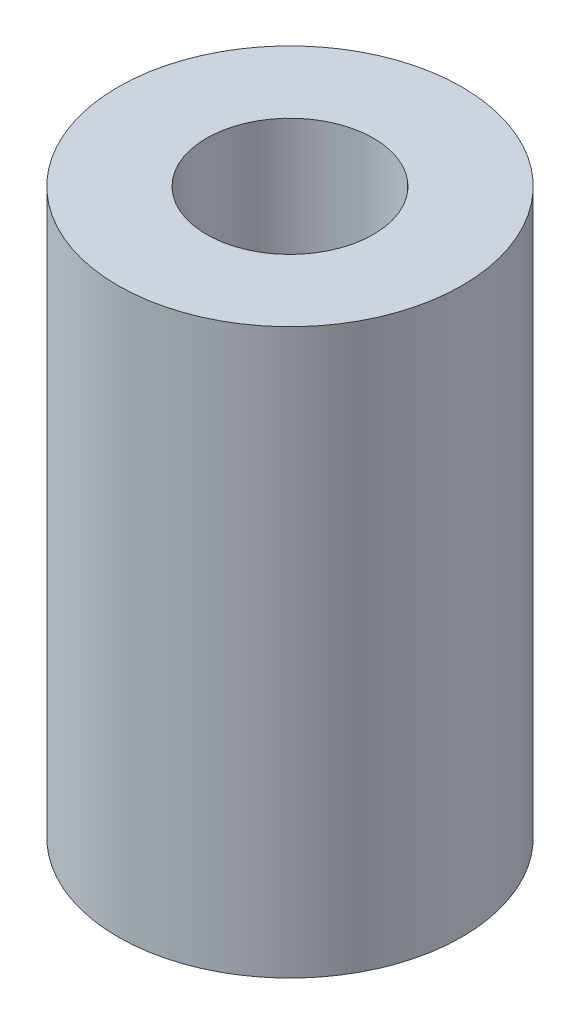
SolidWorks part; units mm, degrees
ref_plane "Front Plane" through (0, 0, 0) normal (0, 0, 1) x (1, 0, 0)
ref_plane "Top Plane" through (0, 0, 0) normal (0, 1, 0) x (1, 0, 0)
ref_plane "Right Plane" through (0, 0, 0) normal (1, 0, 0) x (0, 0, -1)
sketch "Sketch1" plane through (0, 0, 0) normal (0, 0, 1) x (1, 0, 0)
  line L0 (0, 0) -> (0, 10.9277) construction
  line L2 (-3.175, 10.0871) -> (-1.5405, 10.0871)
  line L3 (-3.175, 10.0871) -> (-3.175, -0.3269)
  line L4 (-3.175, -0.3269) -> (-1.5405, -0.3269)
  line L5 (-1.5405, 10.0871) -> (-1.5405, -0.3269)
  dimension "D1" = 10.414
  dimension "D2" = 3.175
revolve "Revolve1" add sketch "Sketch1" angle 360 about L0
